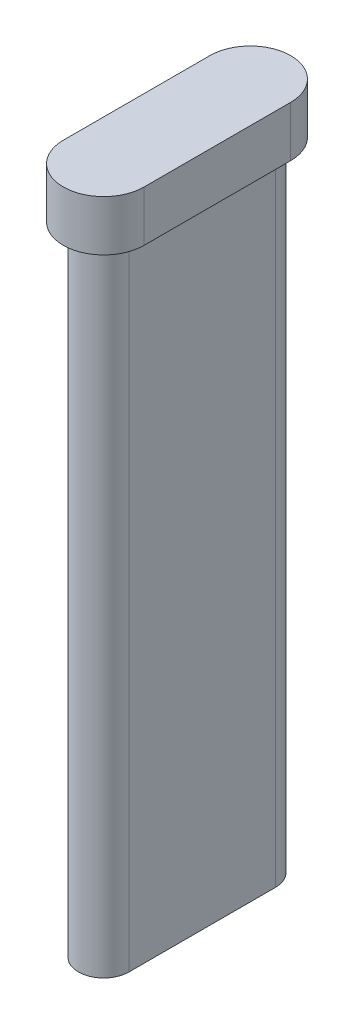
SolidWorks part; units mm, degrees
material "K110"
ref_plane "Front Plane" through (0, 0, 0) normal (0, 0, 1) x (1, 0, 0)
ref_plane "Top Plane" through (0, 0, 0) normal (0, 1, 0) x (1, 0, 0)
ref_plane "Right Plane" through (0, 0, 0) normal (1, 0, 0) x (0, 0, -1)
sketch "Sketch1" plane through (0, 0, 0) normal (0, 1, 0) x (1, 0, 0)
  line L0 (0, -7.25) -> (0, 7.25) construction
  line L1 (-2.5, -7.25) -> (-2.5, 7.25)
  line L2 (2.5, -7.25) -> (2.5, 7.25)
  arc A0 (-2.5, -7.25) -> (2.5, -7.25) centre (0, -7.25) ccw
  arc A1 (2.5, 7.25) -> (-2.5, 7.25) centre (0, 7.25) ccw
  point P2 (0, 0)
  dimension "D2" = 2.5
  dimension "D1" = 14.5
extrude "Boss-Extrude1" add sketch "Sketch1" against normal blind 68
sketch "Sketch2" plane through (0, 0, 0) normal (0, 1, 0) x (1, 0, 0)
  line L4 (4, -7.25) -> (4, 7.25)
  line L5 (-4, 7.25) -> (-4, -7.25)
  line L6 (4, -7.25) -> (4, 7.25)
  line L7 (-4, 7.25) -> (-4, -7.25)
  arc A4 (4, 7.25) -> (-4, 7.25) centre (0, 7.25) ccw
  arc A5 (-4, -7.25) -> (4, -7.25) centre (0, -7.25) ccw
  arc A6 (4, 7.25) -> (-4, 7.25) centre (0, 7.25) ccw
  arc A7 (-4, -7.25) -> (4, -7.25) centre (0, -7.25) ccw
  dimension "D1" = 1.5
extrude "Boss-Extrude2" add sketch "Sketch2" against normal blind 5
